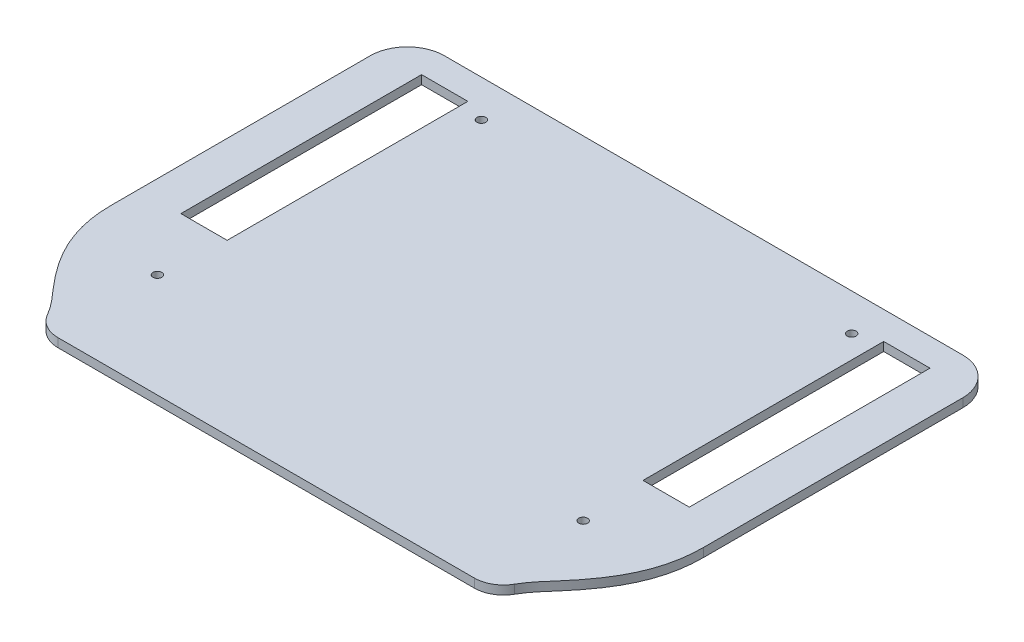
SolidWorks part; units mm, degrees
ref_plane "Front Plane" through (0, 0, 0) normal (0, 0, 1) x (1, 0, 0)
ref_plane "Top Plane" through (0, 0, 0) normal (0, 1, 0) x (1, 0, 0)
ref_plane "Right Plane" through (0, 0, 0) normal (1, 0, 0) x (0, 0, -1)
sketch "Sketch1" plane through (0, 0, 0) normal (0, 1, 0) x (1, 0, 0)
  line L1 (-101.6, -75) -> (101.6, -75)
  line L2 (-101.6, -75) -> (-101.6, 75)
  line L3 (-101.6, 75) -> (101.6, 75)
  line L4 (101.6, -75) -> (101.6, 75)
  line L5 (-101.6, -75) -> (101.6, 75) construction
  line L6 (-101.6, 75) -> (101.6, -75) construction
  point P0 (0, 0)
  dimension "D1" = 203.2
  dimension "D2" = 150
extrude "Boss-Extrude1" add sketch "Sketch1" along normal mid plane 3 contours L3 L4 L1 L2
fillet "Fillet1" radius 12.7 4 edges at (-101.6, 0, 75) (101.6, 0, 75) (101.6, 0, -75) (-101.6, 0, -75)
sketch "Sketch3" plane through (0, -1.5, 0) normal (0, -1, 0) x (1, 0, 0)
  line L0 (87.1875, -65.475) -> (71.3125, -65.475) construction
  line L1 (71.3125, -65.475) -> (71.3125, 17.075) construction
  line L2 (71.3125, 17.075) -> (87.1875, 17.075) construction
  line L3 (87.1875, 17.075) -> (87.1875, -65.475) construction
  line L4 (87.1875, -65.475) -> (71.3125, -65.475)
  line L5 (71.3125, -65.475) -> (71.3125, 17.075)
  line L6 (71.3125, 17.075) -> (87.1875, 17.075)
  line L7 (87.1875, 17.075) -> (87.1875, -65.475)
  circle A0 centre (63.5, -62.3) radius 1.5 construction
  circle A1 centre (73.025, 39.3) radius 1.5 construction
  circle A2 centre (63.5, -62.3) radius 1.5
  circle A3 centre (73.025, 39.3) radius 1.5
extrude "Cut-Extrude2" cut sketch "Sketch3" against normal through all
sketch "Sketch4" plane through (0, -1.5, 0) normal (0, -1, 0) x (1, 0, 0)
  line L0 (101.6, 62.3) -> (101.6, -62.3) construction
  line L1 (-88.9, 75) -> (88.9, 75) construction
  line L2 (101.6, 62.3) -> (101.6, 26.6)
  line L3 (77.6858, 75) -> (88.9, 75)
  arc A0 (101.6, 62.3) -> (88.9, 75) centre (88.9, 62.3) ccw construction
  arc A1 (101.6, 62.3) -> (88.9, 75) centre (88.9, 62.3) ccw
  spline S0 degree 3 poles (-3869.1801, -346.9952) (315.181, 653.975) (18.7785, 135.2468) (151.6426, -8.976) (152.7032, -168.7872) (-3154.1745, -2285.5106) knots -2.717893 -2.717893 -2.717893 -2.717893 0.48462 0.58462 3.952221 3.952221 3.952221 3.952221 only from (66.4897, 119.1138) to (101.6, 26.6) construction
  spline S1 degree 3 poles (77.6858, 75) (78.6161, 72.6453) (81.0825, 67.6164) (92.8364, 54.8577) (101.6, 41.84) (101.6, 26.6) knots 0.409925 0.409925 0.409925 0.409925 0.48462 0.58462 1 1 1 1
extrude "Cut-Extrude3" cut sketch "Sketch4" against normal through all
mirror "Mirror1" about plane through (0, 0, 0) normal (1, 0, 0) of "Cut-Extrude3", "Cut-Extrude2"
fillet "Fillet2" radius 10 2 edges at (77.6858, 0, 75) (-77.6858, 0, 75)
